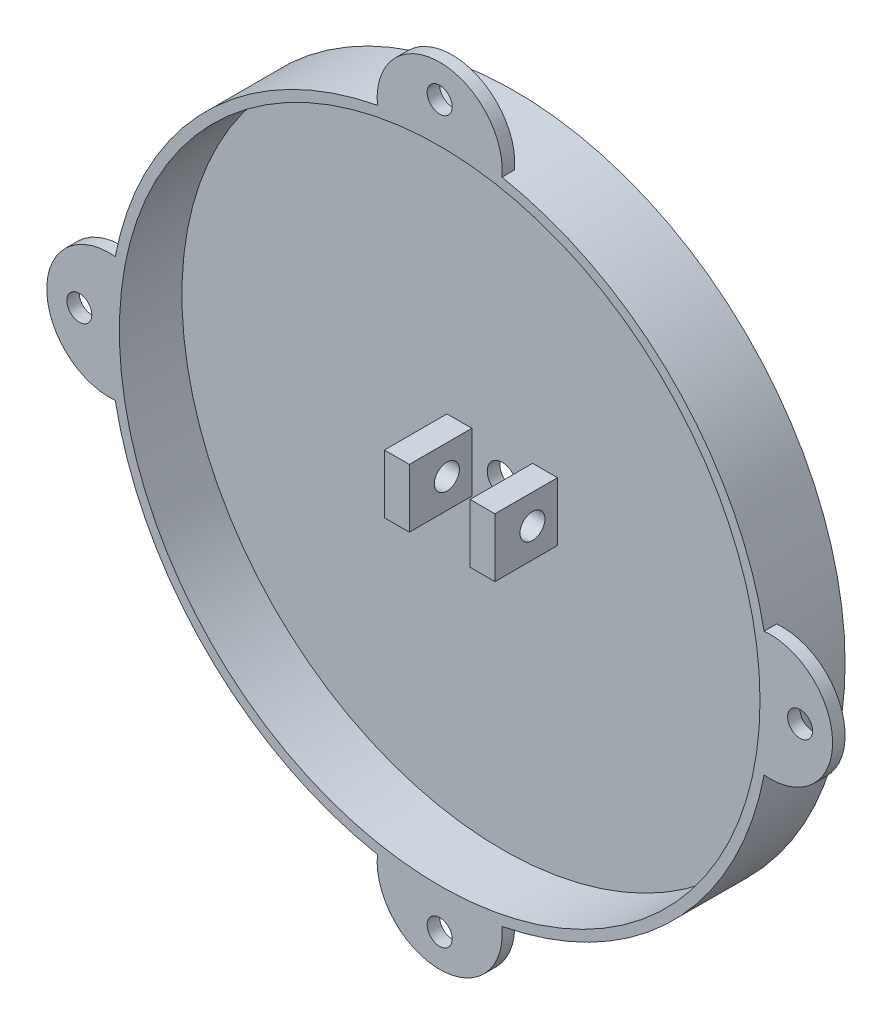
SolidWorks part; units mm, degrees
ref_plane "Front Plane" through (0, 0, 0) normal (0, 0, 1) x (1, 0, 0)
ref_plane "Top Plane" through (0, 0, 0) normal (0, 1, 0) x (1, 0, 0)
ref_plane "Right Plane" through (0, 0, 0) normal (1, 0, 0) x (0, 0, -1)
sketch "Sketch1" plane through (0, 0, 0) normal (0, 0, 1) x (1, 0, 0)
  circle A0 centre (0, 0) radius 132
extrude "Boss-Extrude1" add sketch "Sketch1" along normal blind 5
sketch "Sketch2" plane through (0, 0, 5) normal (0, 0, 1) x (1, 0, 0)
  circle A0 centre (0, 0) radius 128
  circle A1 centre (0, 0) radius 132 construction
  circle A2 centre (0, 0) radius 132
extrude "Boss-Extrude2" add sketch "Sketch2" along normal blind 25
sketch "Sketch3" plane through (0, 0, 5) normal (0, 0, 1) x (1, 0, 0)
  circle A0 centre (0, 0) radius 25
extrude "Boss-Extrude3" add sketch "Sketch3" along normal blind 25
sketch "Sketch4" plane through (0, 0, 30) normal (0, 0, 1) x (1, 0, 0)
  line L1 (-12.1299, -26.8174) -> (12.1299, -26.8174)
  line L2 (-12.1299, -26.8174) -> (-12.1299, 26.8174)
  line L3 (-12.1299, 26.8174) -> (12.1299, 26.8174)
  line L4 (12.1299, -26.8174) -> (12.1299, 26.8174)
  line L5 (-12.1299, -26.8174) -> (12.1299, 26.8174) construction
  line L6 (-12.1299, 26.8174) -> (12.1299, -26.8174) construction
  point P0 (0, 0)
extrude "Cut-Extrude1" cut sketch "Sketch4" against normal blind 25
sketch "Sketch5" plane through (0, 0, 30) normal (0, 0, 1) x (1, 0, 0)
  line L1 (-22.0752, -35.0158) -> (22.0752, -35.0158)
  line L2 (-22.0752, -35.0158) -> (-22.0752, 35.0158)
  line L3 (-22.0752, 35.0158) -> (22.0752, 35.0158)
  line L4 (22.0752, -35.0158) -> (22.0752, 35.0158)
  line L5 (-22.0752, -35.0158) -> (22.0752, 35.0158) construction
  line L6 (-22.0752, 35.0158) -> (22.0752, -35.0158) construction
  line L7 (-26.6609, -38.5433) -> (26.6609, -38.5433)
  line L8 (-26.6609, -38.5433) -> (-26.6609, 38.5433)
  line L9 (-26.6609, 38.5433) -> (26.6609, 38.5433)
  line L10 (26.6609, -38.5433) -> (26.6609, 38.5433)
  line L11 (-26.6609, -38.5433) -> (26.6609, 38.5433) construction
  line L12 (-26.6609, 38.5433) -> (26.6609, -38.5433) construction
  point P0 (0, 0)
  point P6 (0, 0)
extrude "Cut-Extrude2" cut sketch "Sketch5" against normal blind 25
sketch "Sketch6" plane through (0, 0, 30) normal (0, 0, 1) x (1, 0, 0)
  line L1 (-22.0752, -11.7339) -> (22.0752, -11.7339)
  line L2 (-22.0752, -11.7339) -> (-22.0752, 11.7339)
  line L3 (-22.0752, 11.7339) -> (22.0752, 11.7339)
  line L4 (22.0752, -11.7339) -> (22.0752, 11.7339)
  line L5 (-22.0752, -11.7339) -> (22.0752, 11.7339) construction
  line L6 (-22.0752, 11.7339) -> (22.0752, -11.7339) construction
  line L7 (-28.5502, -23.4113) -> (28.5502, -23.4113)
  line L8 (-28.5502, -23.4113) -> (-28.5502, 23.4113)
  line L9 (-28.5502, 23.4113) -> (28.5502, 23.4113)
  line L10 (28.5502, -23.4113) -> (28.5502, 23.4113)
  line L11 (-28.5502, -23.4113) -> (28.5502, 23.4113) construction
  line L12 (-28.5502, 23.4113) -> (28.5502, -23.4113) construction
  point P0 (0, 0)
  point P7 (0, 0)
extrude "Cut-Extrude4" cut sketch "Sketch6" against normal blind 25
sketch "Sketch7" plane through (22.0752, 0, 0) normal (1, 0, 0) x (0, 0, -1)
  line L0 (-30, 0) -> (-15, 0)
  line L1 (-30, 132) -> (-30, -132) construction
  circle A0 centre (-15, 0) radius 5
extrude "Cut-Extrude5" cut sketch "Sketch7" against normal blind 60 contours A0
sketch "Sketch8" plane through (0, 0, 5) normal (0, 0, 1) x (1, 0, 0)
  circle A0 centre (0, 0) radius 6
extrude "Cut-Extrude6" cut sketch "Sketch8" against normal mid plane 60
sketch "Sketch9" plane through (0, 0, 30) normal (0, 0, 1) x (1, 0, 0)
  arc A0 (-129.6326, 24.8877) -> (-129.6326, -24.8877) centre (-132, 0) ccw
  circle A1 centre (0, 0) radius 132 construction
  circle A2 centre (-144.0007, 0) radius 5
  circle A3 centre (0, 0) radius 132
  circle M1 centre (0, 0) radius 132
extrude "Boss-Extrude4" add sketch "Sketch9" against normal blind 5 contours A0 A2 M1
pattern_circular "CirPattern1" count 4 over 360 about axis through (0, 0, 0) along (0, 0, 1) of "Boss-Extrude4"
